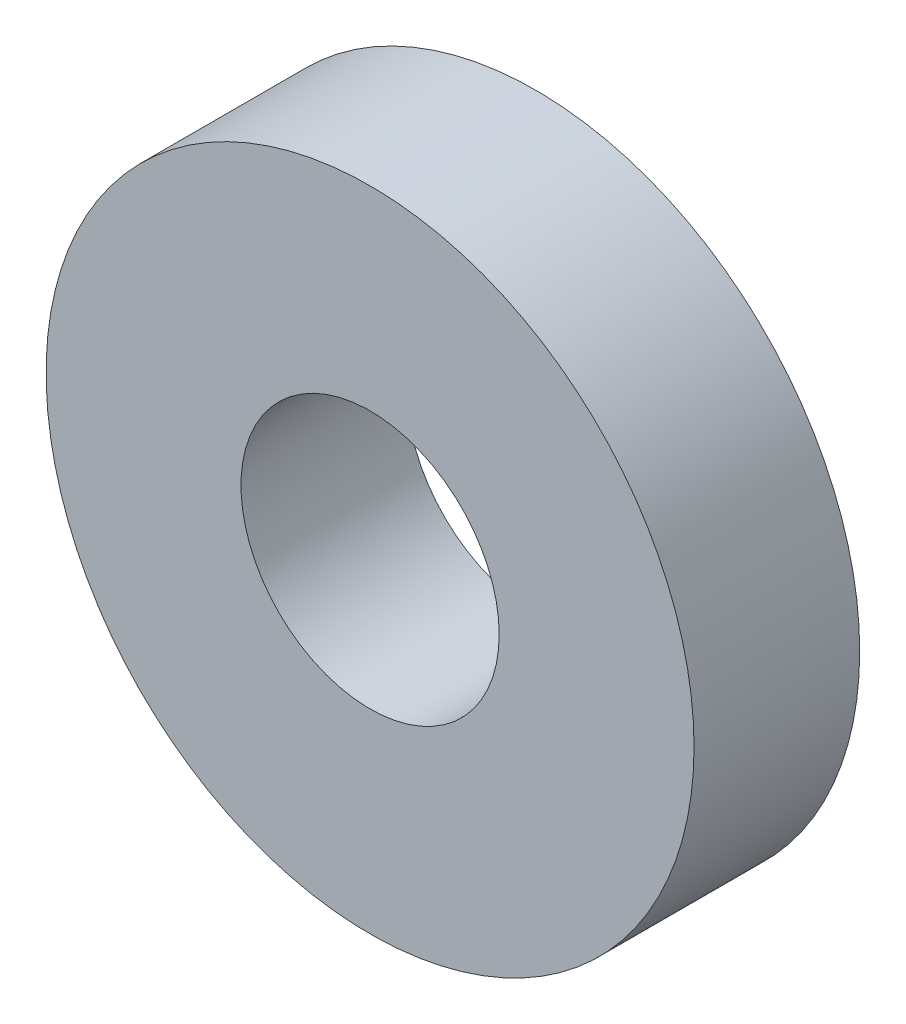
SolidWorks part; units mm, degrees
ref_plane "Plan de face" through (0, 0, 0) normal (0, 0, 1) x (1, 0, 0)
ref_plane "Plan de dessus" through (0, 0, 0) normal (0, 1, 0) x (1, 0, 0)
ref_plane "Plan de droite" through (0, 0, 0) normal (1, 0, 0) x (0, 0, -1)
sketch "Esquisse1" plane through (0, 0, 0) normal (0, 0, 1) x (1, 0, 0)
  circle A0 centre (0, 0) radius 2.65
  circle A1 centre (0, 0) radius 6.65
  dimension "D1" = 5.3
  dimension "D2" = 13.3
extrude "Boss.-Extru.1" add sketch "Esquisse1" along normal blind 3.4
equation "\"D2@Esquisse1\"=\"D1@Esquisse1\"+2*4"
